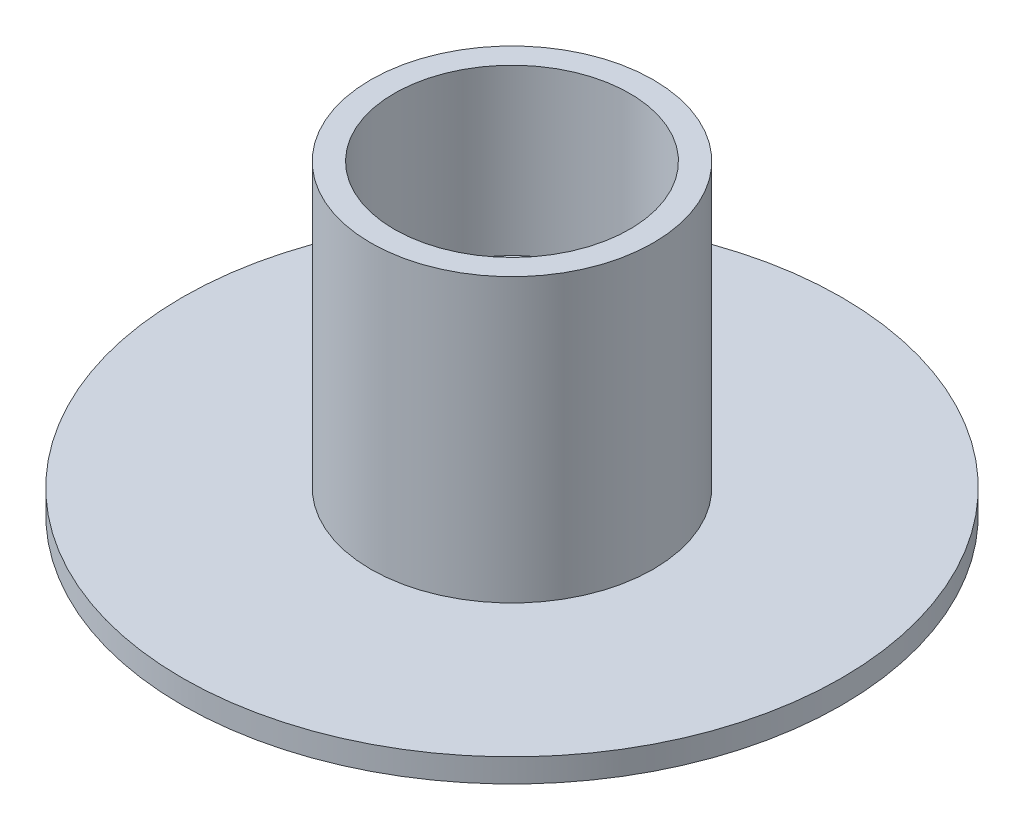
SolidWorks part; units mm, degrees
ref_plane "Alzado" through (0, 0, 0) normal (0, 0, 1) x (1, 0, 0)
ref_plane "Planta" through (0, 0, 0) normal (0, 1, 0) x (1, 0, 0)
ref_plane "Vista lateral" through (0, 0, 0) normal (1, 0, 0) x (0, 0, -1)
sketch "Croquis1" plane through (0, 0, 0) normal (0, 1, 0) x (1, 0, 0)
  circle A0 centre (0, 0) radius 70
  dimension "D1" = 140
extrude "Saliente-Extruir1" add sketch "Croquis1" along normal blind 5
sketch "Croquis2" plane through (0, 5, 0) normal (0, 1, 0) x (1, 0, 0)
  circle A0 centre (0, 0) radius 30
  dimension "D1" = 60
extrude "Saliente-Extruir2" add sketch "Croquis2" along normal blind 60
sketch "Croquis5" plane through (0, 0, 0) normal (0, -1, 0) x (1, 0, 0)
  circle A0 centre (0, 0) radius 5.25
  dimension "D1" = 10.5
extrude "Cortar-Extruir5" cut sketch "Croquis5" against normal blind 10
sketch "Croquis7" plane through (0, 65, 0) normal (0, 1, 0) x (1, 0, 0)
  circle A0 centre (0, 0) radius 25
  dimension "D1" = 50
extrude "Cortar-Extruir6" cut sketch "Croquis7" against normal blind 35
